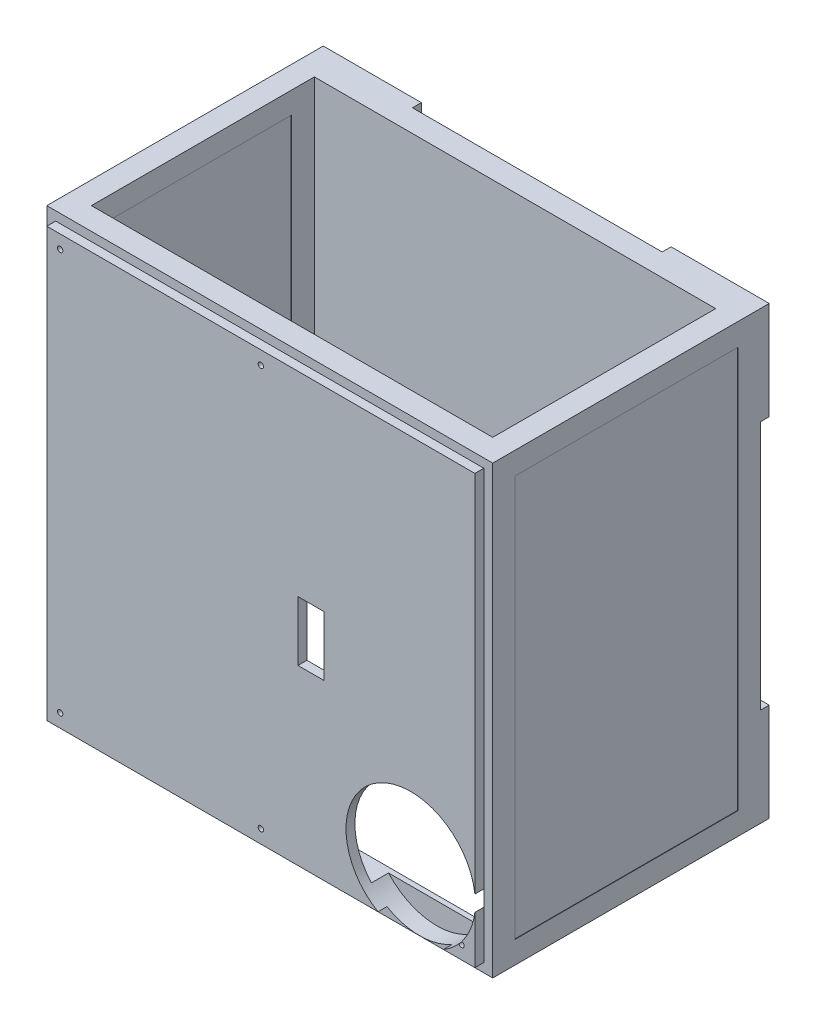
SolidWorks part; units mm, degrees
ref_plane "前视基准面" through (0, 0, 0) normal (0, 0, 1) x (1, 0, 0)
ref_plane "上视基准面" through (0, 0, 0) normal (0, 1, 0) x (1, 0, 0)
ref_plane "右视基准面" through (0, 0, 0) normal (1, 0, 0) x (0, 0, -1)
sketch "草图1" plane through (0, 0, 0) normal (0, 0, 1) x (1, 0, 0)
  line L0 (950, 27.9086) -> (950, -972.0914)
  line L1 (-50, 27.9086) -> (950, 27.9086)
  line L2 (-50, 27.9086) -> (-50, -972.0914)
  line L3 (-50, -972.0914) -> (950, -972.0914)
  line L4 (450, 27.9086) -> (450, -972.0914) construction
  dimension "D1" = 500
  dimension "D2" = 1000
extrude "凸台-拉伸1" add sketch "草图1" along normal blind 600
sketch "草图2" plane through (0, -972.0914, 0) normal (0, -1, 0) x (1, 0, 0)
  line L0 (-50, 0) -> (950, 0) construction
  line L1 (950, 600) -> (950, 0) construction
  line L2 (-50, 600) -> (-50, 0) construction
  line L3 (-50, 600) -> (950, 600) construction
  line L4 (-50, 0) -> (950, 0)
  line L5 (950, 600) -> (950, 0)
  line L6 (-50, 600) -> (-50, 0)
  line L7 (-50, 600) -> (950, 600)
  line L8 (0, 550) -> (900, 550)
  line L9 (900, 550) -> (900, 50)
  line L10 (0, 50) -> (900, 50)
  line L11 (0, 550) -> (0, 50)
  dimension "D1" = 50
extrude "切除-拉伸3" cut sketch "草图2" against normal blind 1 contours L8 L9 L10 L11
sketch "草图5" plane through (950, 0, 0) normal (1, 0, 0) x (0, 0, -1)
  line L0 (-50, -22.0914) -> (-550, -22.0914)
  line L1 (-550, -22.0914) -> (-550, -922.0914)
  line L2 (-550, -922.0914) -> (-50, -922.0914)
  line L3 (-50, -922.0914) -> (-50, -22.0914)
  line L4 (0, -972.0914) -> (0, 27.9086)
  line L5 (0, 27.9086) -> (-600, 27.9086)
  line L6 (-600, 27.9086) -> (-600, -972.0914)
  line L7 (-600, -972.0914) -> (0, -972.0914)
  line L8 (0, -972.0914) -> (0, 27.9086)
  line L9 (0, 27.9086) -> (-600, 27.9086)
  line L10 (-600, 27.9086) -> (-600, -972.0914)
  line L11 (-600, -972.0914) -> (0, -972.0914)
  dimension "D1" = 0
  dimension "D2" = 50
extrude "切除-拉伸4" cut sketch "草图5" against normal blind 1 contours L2 L3 L0 L1
ref_plane "基准面4" through (450, 0, 0) normal (-1, 0, 0) x (0, 0, 1)
ref_plane "基准面5" through (0, -472.0914, 0) normal (0, 1, 0) x (1, 0, 0)
mirror "镜向1" about plane through (0, -472.0914, 0) normal (0, 1, 0) of "切除-拉伸3"
mirror "镜向2" about plane through (450, 0, 0) normal (-1, 0, 0) of "切除-拉伸4"
sketch "草图8" plane through (0, 0, 600) normal (0, 0, 1) x (1, 0, 0)
  line L8 (-30, 7.9086) -> (-30, -952.0914)
  line L9 (-30, -952.0914) -> (930, -952.0914)
  line L10 (930, -952.0914) -> (930, 7.9086)
  line L11 (930, 7.9086) -> (-30, 7.9086)
  line L12 (-30, 7.9086) -> (-30, -952.0914)
  line L13 (-30, -952.0914) -> (930, -952.0914)
  line L14 (930, -952.0914) -> (930, 7.9086)
  line L15 (930, 7.9086) -> (-30, 7.9086)
  dimension "D1" = 20
extrude "凸台-拉伸5" add sketch "草图8" along normal blind 20 contours L12 L13 L14 L15
sketch "草图9" plane through (0, -971.0914, 0) normal (0, -1, 0) x (1, 0, 0)
  line L0 (450, 550) -> (450, 50) construction
  line L1 (0, 550) -> (900, 550) construction
  line L2 (0, 50) -> (900, 50) construction
  line L3 (450, 550) -> (900, 550)
  line L4 (900, 550) -> (900, 50) construction
  line L5 (0, 550) -> (900, 550) construction
  line L6 (900, 550) -> (900, 50)
  line L7 (900, 50) -> (450, 50)
  line L8 (450, 50) -> (450, 550)
extrude "切除-拉伸5" cut sketch "草图9" against normal blind 20
mirror "镜向3" about plane through (0, -472.0914, 0) normal (0, 1, 0) of "切除-拉伸5"
sketch "草图10" plane through (0, 0, 620) normal (0, 0, 1) x (1, 0, 0)
  circle A0 centre (450, -922.0914) radius 6
  circle A1 centre (900, -922.0914) radius 6
  circle A2 centre (0, -922.0914) radius 6
  circle A3 centre (0, -22.0914) radius 6
  circle A4 centre (450, -22.0914) radius 6
  point P23 (900, -22.0914)
sketch "草图11" plane through (0, 0, 0) normal (0, 0, -1) x (-1, 0, 0)
  line L0 (50, -192.0914) -> (-20, -192.0914)
  line L1 (-170, -972.0914) -> (-170, -902.0914)
  line L2 (50, -752.0914) -> (-20, -752.0914)
  line L3 (-730, -972.0914) -> (-730, -902.0914)
  line L6 (50, 27.9086) -> (-170, 27.9086)
  line L7 (-170, 27.9086) -> (-170, -42.0914)
  line L8 (-20, -902.0914) -> (-20, -42.0914)
  line L9 (-20, -42.0914) -> (-880, -42.0914)
  line L10 (-880, -42.0914) -> (-880, -902.0914)
  line L11 (-880, -902.0914) -> (-20, -902.0914)
  line L12 (-20, -842.0914) -> (-20, -752.0914)
  line L13 (-80, -42.0914) -> (-170, -42.0914)
  line L14 (-880, -102.0914) -> (-880, -192.0914)
  line L15 (-820, -902.0914) -> (-730, -902.0914)
  line L16 (50, -972.0914) -> (50, 27.9086)
  line L17 (50, 27.9086) -> (-950, 27.9086)
  line L18 (-950, 27.9086) -> (-950, -972.0914)
  line L19 (-950, -972.0914) -> (50, -972.0914)
  line L20 (50, -972.0914) -> (50, -752.0914)
  line L21 (50, 27.9086) -> (-170, 27.9086)
  line L22 (-950, 27.9086) -> (-950, -192.0914)
  line L23 (-950, -972.0914) -> (-730, -972.0914)
  line L24 (50, 27.9086) -> (50, -192.0914)
  line L25 (-950, -752.0914) -> (-880, -752.0914)
  line L26 (-950, -192.0914) -> (-880, -192.0914)
  line L27 (-730, 27.9086) -> (-730, -42.0914)
  line L28 (-730, -42.0914) -> (-820, -42.0914)
  line L29 (-730, 27.9086) -> (-950, 27.9086)
  line L30 (-20, -192.0914) -> (-20, -102.0914)
  line L31 (50, -192.0914) -> (50, 27.9086)
  line L32 (-170, -902.0914) -> (-80, -902.0914)
  line L33 (-170, -972.0914) -> (50, -972.0914)
  line L34 (-880, -752.0914) -> (-880, -842.0914)
  line L35 (-950, -752.0914) -> (-950, -972.0914)
  arc A0 (-20, -102.0914) -> (-80, -42.0914) centre (-80, -102.0914) ccw
  arc A1 (-880, -102.0914) -> (-820, -42.0914) centre (-820, -102.0914) cw
  arc A2 (-820, -902.0914) -> (-880, -842.0914) centre (-820, -842.0914) cw
  arc A3 (-20, -842.0914) -> (-80, -902.0914) centre (-80, -842.0914) cw
  line M15 (50, -972.0914) -> (50, 27.9086)
  line M16 (50, 27.9086) -> (-950, 27.9086)
  line M17 (-950, 27.9086) -> (-950, -972.0914)
  line M18 (-950, -972.0914) -> (50, -972.0914)
  dimension "D3" = 60
  dimension "D4" = 60
  dimension "D5" = 60
  dimension "D6" = 60
  dimension "D1" = 70
  dimension "D2" = 0
extrude "凸台-拉伸7" add sketch "草图11" along normal blind 20 contours L14 A1 L28 L27 L26 M16 M17 | A0 L30 L0 L7 L13 M15 M16 | L12 A3 L32 L1 L2 M18 M15 | L15 A2 L34 L25 L3 M17 M18
extrude "切除-拉伸6" cut sketch "草图10" against normal blind 50
scale "缩放比例3" scale about centroid uniform scaling yes scale factor 0.7
ref_plane "基准面6" through (0, 0, 512.4818) normal (0, 0, 1) x (1, 0, 0)
sketch "草图12" plane through (0, 0, 512.4818) normal (0, 0, 1) x (1, 0, 0)
  line L0 (785.0049, -136.0902) -> (113.0049, -136.0902) construction
  line L1 (785.0049, -136.0902) -> (113.0049, -136.0902)
  line L2 (785.0049, -808.0902) -> (785.0049, -136.0902) construction
  line L3 (113.0049, -808.0902) -> (785.0049, -808.0902) construction
  line L4 (113.0049, -136.0902) -> (113.0049, -808.0902) construction
  line L5 (785.0049, -808.0902) -> (785.0049, -136.0902)
  line L6 (113.0049, -808.0902) -> (785.0049, -808.0902)
  line L7 (113.0049, -136.0902) -> (113.0049, -808.0902)
sketch "草图13" plane through (0, 0, 512.4818) normal (0, 0, 1) x (1, 0, 0)
  line L8 (765.0049, -156.0902) -> (133.0049, -156.0902)
  line L9 (133.0049, -156.0902) -> (133.0049, -788.0902)
  line L10 (133.0049, -788.0902) -> (765.0049, -788.0902)
  line L11 (765.0049, -788.0902) -> (765.0049, -156.0902)
  line L12 (765.0049, -156.0902) -> (133.0049, -156.0902)
  line L13 (133.0049, -156.0902) -> (133.0049, -788.0902)
  line L14 (133.0049, -788.0902) -> (765.0049, -788.0902)
  line L15 (765.0049, -788.0902) -> (765.0049, -156.0902)
  dimension "D1" = 20
extrude "切除-拉伸9" cut sketch "草图13" against normal blind 349
sketch "草图14" plane through (0, 0, 526.4818) normal (0, 0, 1) x (1, 0, 0)
  line L1 (507.1876, -442.4293) -> (548.1091, -442.4293)
  line L2 (507.1876, -442.4293) -> (507.1876, -536.0557)
  line L3 (507.1876, -536.0557) -> (548.1091, -536.0557)
  line L4 (548.1091, -442.4293) -> (548.1091, -536.0557)
extrude "切除-拉伸10" cut sketch "草图14" against normal blind 48
sketch "草图16" plane through (0, -122.7902, 0) normal (0, 1, 0) x (1, 0, 0)
  line L0 (764.0049, -477.4818) -> (449.0049, -477.4818) construction
  line L1 (134.0049, -127.4818) -> (764.0049, -127.4818)
  line L2 (134.0049, -127.4818) -> (134.0049, -477.4818)
  line L3 (134.0049, -477.4818) -> (764.0049, -477.4818)
  line L4 (764.0049, -127.4818) -> (764.0049, -477.4818)
  line L5 (764.0049, -127.4818) -> (764.0049, -477.4818) construction
extrude "切除-拉伸11" cut sketch "草图16" against normal blind 952
sketch "草图17" plane through (0, 0, 526.4818) normal (0, 0, 1) x (1, 0, 0)
  line L0 (427.2105, -720.4335) -> (745.9581, -720.4335) construction
  line L1 (427.2105, -741.2335) -> (427.2105, -699.6335) construction
  line L2 (684.2085, -720.4335) -> (684.2085, -583.5224) construction
  circle A0 centre (684.2085, -720.4335) radius 101.5593
  dimension "D1" = 203.1187
extrude "切除-拉伸14" cut sketch "草图17" along normal blind 30 and the other way blind 41
scale "缩放比例4" scale about centroid uniform scaling yes scale factor 1.3
